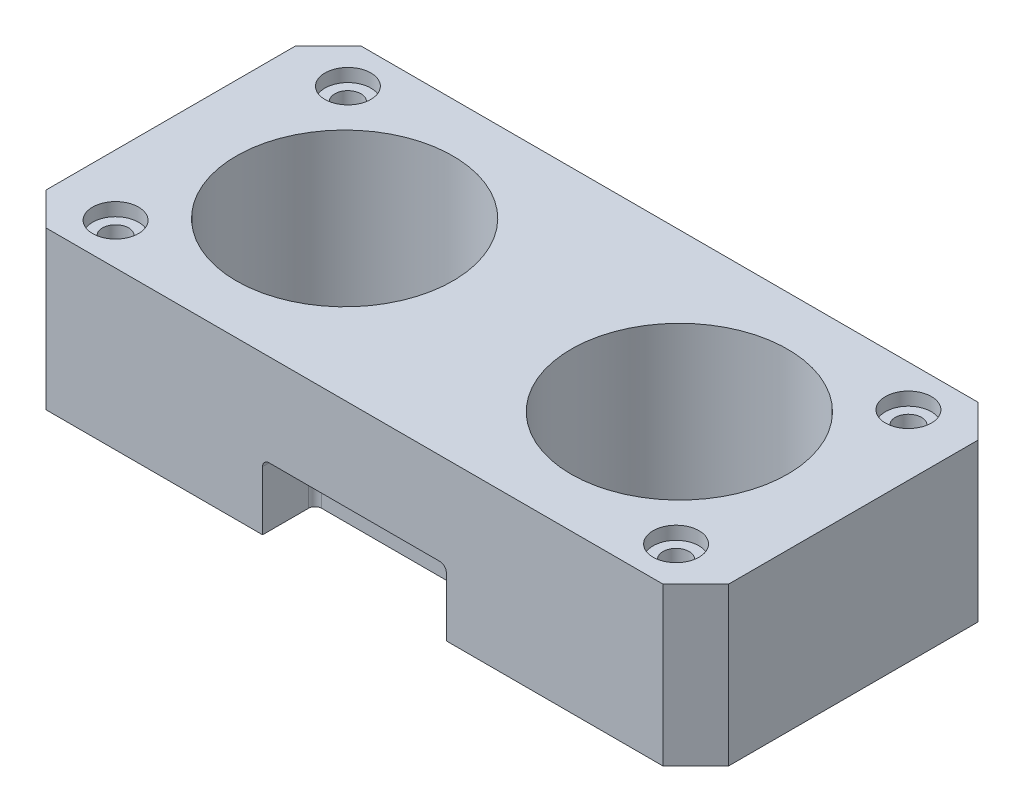
SolidWorks part; units mm, degrees
ref_plane "Front Plane" through (0, 0, 0) normal (0, 0, 1) x (1, 0, 0)
ref_plane "Top Plane" through (0, 0, 0) normal (0, 1, 0) x (1, 0, 0)
ref_plane "Right Plane" through (0, 0, 0) normal (1, 0, 0) x (0, 0, -1)
sketch "Sketch1" plane through (0, 0, 0) normal (0, 1, 0) x (1, 0, 0)
  line L0 (-12.75, 0) -> (12.75, 0) construction
  line L1 (-26, 12) -> (26, 12)
  line L2 (-26, 12) -> (-26, -12)
  line L3 (-26, -12) -> (26, -12)
  line L4 (26, 12) -> (26, -12)
  line L5 (-26, 12) -> (26, -12) construction
  line L6 (-26, -12) -> (26, 12) construction
  circle A0 centre (12.75, 0) radius 8.25
  circle A1 centre (-12.75, 0) radius 8.25
  point P0 (0, 0)
  point P9 (0, 0)
  dimension "D3" = 16.5
  dimension "D1" = 52
  dimension "D2" = 24
  dimension "D4" = 25.5
extrude "Boss-Extrude1" add sketch "Sketch1" along normal blind 12
sketch "Sketch2" plane through (0, 12, 0) normal (0, 1, 0) x (1, 0, 0)
  line L1 (-21.35, 8.85) -> (21.35, 8.85) construction
  line L2 (-21.35, 8.85) -> (-21.35, -8.85) construction
  line L3 (-21.35, -8.85) -> (21.35, -8.85) construction
  line L4 (21.35, 8.85) -> (21.35, -8.85) construction
  line L5 (-21.35, 8.85) -> (21.35, -8.85) construction
  line L6 (-21.35, -8.85) -> (21.35, 8.85) construction
  circle A0 centre (-21.35, 8.85) radius 1
  circle A1 centre (21.35, 8.85) radius 1
  circle A2 centre (21.35, -8.85) radius 1
  circle A3 centre (-21.35, -8.85) radius 1
  point P0 (0, 0)
  dimension "D3" = 2
  dimension "D1" = 17.7
  dimension "D2" = 42.7
extrude "Cut-Extrude1" cut sketch "Sketch2" against normal through all
sketch "Sketch3" plane through (0, 12, 0) normal (0, 1, 0) x (1, 0, 0)
  circle A20 centre (-21.35, 8.85) radius 1.75
  circle A21 centre (21.35, 8.85) radius 1.75
  circle A23 centre (21.35, -8.85) radius 1.75
  circle A24 centre (-21.35, -8.85) radius 1.75
  dimension "D1" = 3.5
extrude "Cut-Extrude2" cut sketch "Sketch3" against normal blind 1
sketch "Sketch4" plane through (0, 0, 0) normal (0, -1, 0) x (1, 0, 0)
  line L0 (26, -12) -> (-26, -12) construction
  line L1 (-6, -12) -> (6, -12)
  line L2 (-6, -12) -> (-6, -5)
  line L3 (-6, -5) -> (6, -5)
  line L4 (6, -12) -> (6, -5)
  line L5 (0, -5) -> (0, 0)
  line M14 (-26, -12) -> (26, -12)
  dimension "D1" = 7
  dimension "D2" = 12
extrude "Cut-Extrude3" cut sketch "Sketch4" against normal blind 5 contours L4 L3 L2 M14
fillet "Fillet3" radius 0.5 5 edges at (-6, 5, -8.5) (6, 5, -8.5) (6, 2.5, -5) (0, 5, -5) (-6, 2.5, -5)
chamfer "Chamfer1" distance 2.5 4 edges at (26, 6, 12) (26, 6, -12) (-26, 6, -12) (-26, 6, 12)
sketch "Sketch5" plane through (0, 0, 0) normal (0, -1, 0) x (1, 0, 0)
  line L0 (-23.5, 12) -> (23.5, 12) construction
  line L1 (-7, 16) -> (7, 16)
  line L2 (-7, 16) -> (-7, 8)
  line L3 (-7, 8) -> (7, 8)
  line L4 (7, 16) -> (7, 8)
  line L5 (-7, 16) -> (7, 8) construction
  line L6 (-7, 8) -> (7, 16) construction
  point P0 (0, 12)
  dimension "D1" = 8
  dimension "D2" = 14
extrude "Cut-Extrude4" cut sketch "Sketch5" against normal up to surface (5 mm away) up to face at (0, 5, -8.75)
fillet "Fillet4" radius 0.5 5 edges at (7, 2.5, 8) (7, 5, 10) (-7, 5, 10) (-7, 2.5, 8) (0, 5, 8)
